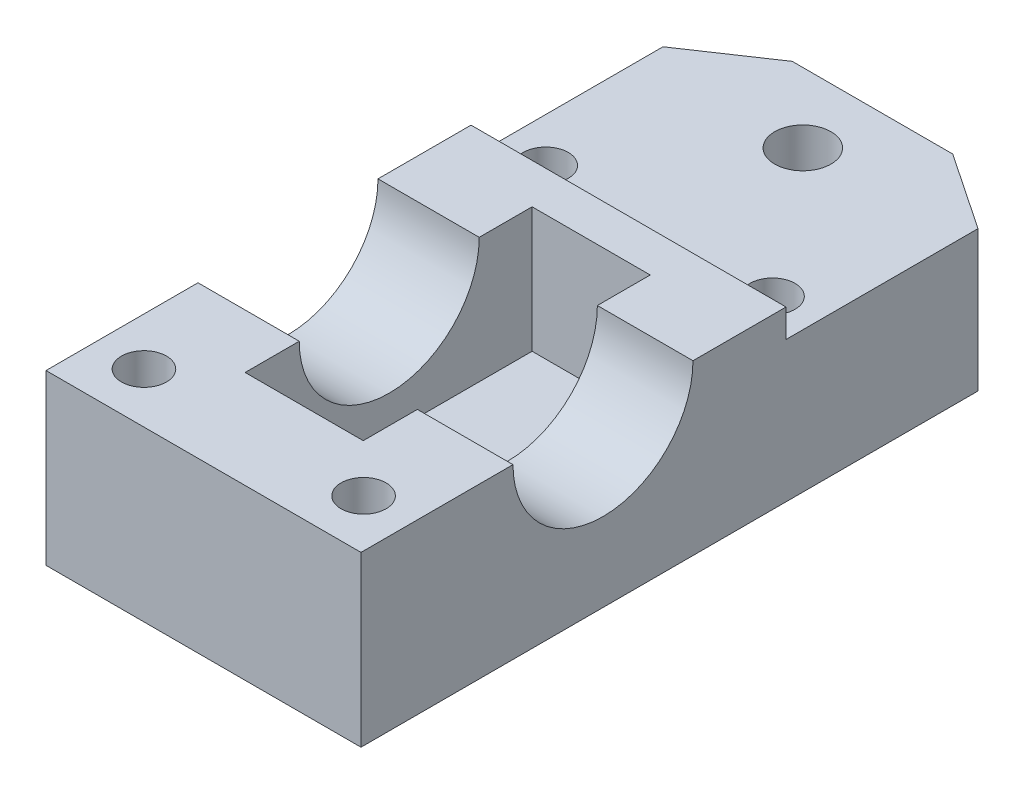
SolidWorks part; units mm, degrees
ref_plane "Спереди" through (0, 0, 0) normal (0, 0, 1) x (1, 0, 0)
ref_plane "Сверху" through (0, 0, 0) normal (0, 1, 0) x (1, 0, 0)
ref_plane "Справа" through (0, 0, 0) normal (1, 0, 0) x (0, 0, -1)
sketch "Эскиз1" plane through (0, 0, 0) normal (0, 1, 0) x (1, 0, 0)
  line L0 (14, 26.9642) -> (7.1317, 31.5859)
  line L1 (-7.1317, 31.5859) -> (7.1317, 31.5859)
  line L2 (-14, 26.9642) -> (-14, -27.8803)
  line L3 (-14, -27.8803) -> (14, -27.8803)
  line L4 (14, 26.9642) -> (14, -27.8803)
  line L5 (0, 20.8048) -> (0, 42.0595) construction
  line L6 (-14, 26.9642) -> (-7.1317, 31.5859)
  circle A0 centre (0, 25.3936) radius 2.5
extrude "Вытянуть1" add sketch "Эскиз1" along normal blind 15
sketch "Эскиз4" plane through (14, 0, 0) normal (1, 0, 0) x (0, 0, -1)
  line L0 (-19.1819, 15) -> (-19.1819, 3.8769)
  line L1 (-19.1819, 3.8769) -> (6.3284, 3.8769)
  line L2 (6.3284, 3.8769) -> (6.3284, 15)
  line L3 (6.3284, 15) -> (-19.1819, 15)
  line L4 (26.9642, 15) -> (-27.8803, 15) construction
extrude "Вырез-Вытянуть1" cut sketch "Эскиз4" against normal blind 10.5 from offset 8.5 offset against normal yes
sketch "Эскиз5" plane through (14, 0, 0) normal (1, 0, 0) x (0, 0, -1)
  line L0 (26.9642, 15) -> (-27.8803, 15) construction
  line L1 (-6.4268, 3.8769) -> (-6.4268, 12.0029) construction
  circle A0 centre (-6.3703, 15) radius 8
extrude "Вытянуть2" cut sketch "Эскиз5" against normal through all
sketch "Эскиз6" plane through (0, 15, 0) normal (0, 1, 0) x (1, 0, 0)
  line L0 (0, 27.8803) -> (0, 36.0822) construction
  circle A0 centre (-9.761, -23.4116) radius 2
  circle A1 centre (9.761, -23.4116) radius 2
extrude "Вытянуть3" cut sketch "Эскиз6" against normal through all
sketch "Эскиз7" plane through (-14, 0, 0) normal (-1, 0, 0) x (0, 0, 1)
  line L0 (-9.8999, 18.9664) -> (-9.8999, 12.5)
  line L1 (-6.3284, 15) -> (-40.2392, 15) construction
  line L2 (-31.5859, 12.5) -> (-9.8999, 12.5)
  line L3 (-31.5859, 15) -> (-31.5859, 0) construction
  line L4 (-31.5859, 12.5) -> (-31.5859, 18.9664)
  line L5 (-31.5859, 18.9664) -> (-9.8999, 18.9664)
  dimension "D1" = 2.5
extrude "Вырез-Вытянуть2" cut sketch "Эскиз7" against normal through all
sketch "Эскиз8" plane through (0, 12.5, 0) normal (0, 1, 0) x (1, 0, 0)
  line L0 (0, 25.5426) -> (0, 27.9974) construction
  circle A0 centre (-10.08, 12.6211) radius 2
  circle A1 centre (10.08, 12.6211) radius 2
extrude "Вытянуть4" cut sketch "Эскиз8" against normal through all
